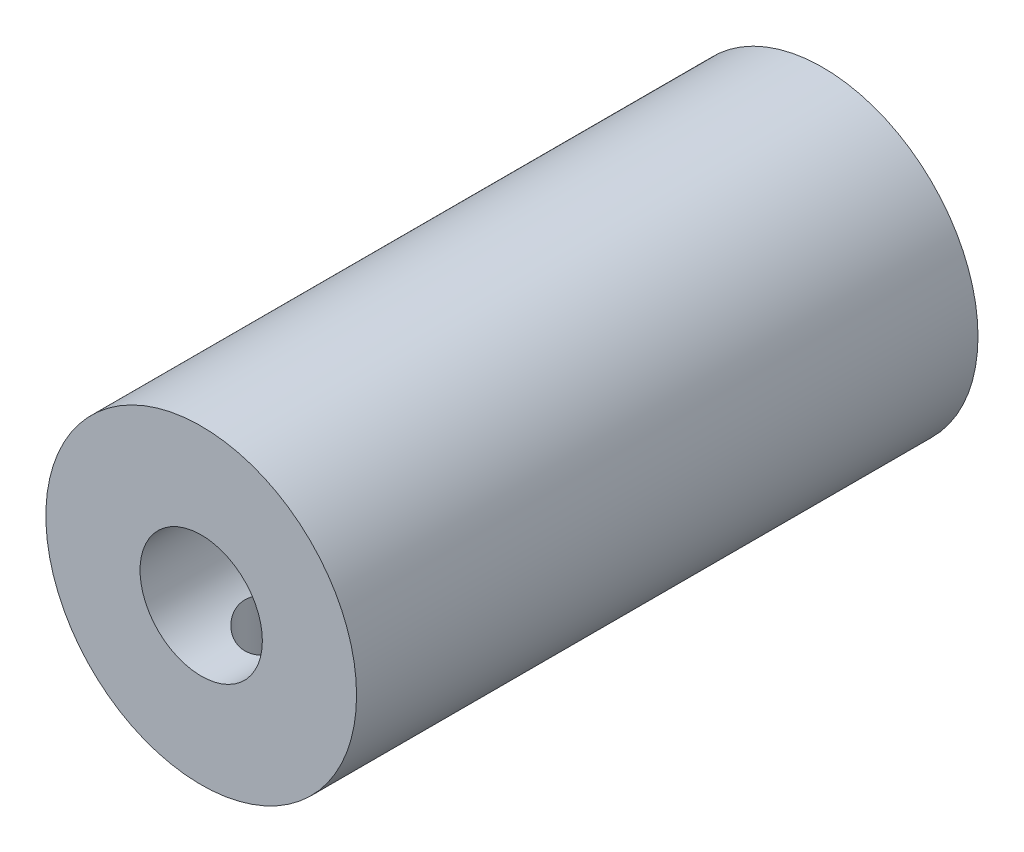
SolidWorks part; units mm, degrees
ref_plane "Front Plane" through (0, 0, 0) normal (0, 0, 1) x (1, 0, 0)
ref_plane "Top Plane" through (0, 0, 0) normal (0, 1, 0) x (1, 0, 0)
ref_plane "Right Plane" through (0, 0, 0) normal (1, 0, 0) x (0, 0, -1)
sketch "Sketch1" plane through (0, 0, 0) normal (0, 0, 1) x (1, 0, 0)
  circle A0 centre (0, 0) radius 6.35
  dimension "D1" = 12.7
extrude "Boss-Extrude1" add sketch "Sketch1" along normal blind 25.4
sketch "Sketch2" plane through (0, 0, 25.4) normal (0, 0, 1) x (1, 0, 0)
  circle A0 centre (0, 0) radius 2.5
  dimension "D1" = 5
extrude "Cut-Extrude1" cut sketch "Sketch2" against normal blind 12.7
sketch "Sketch3" plane through (0, 0, 0) normal (0, 0, -1) x (-1, 0, 0)
  circle A0 centre (0, 0) radius 3.175
  dimension "D1" = 6.35
extrude "Cut-Extrude2" cut sketch "Sketch3" against normal blind 12.7
sketch "Sketch4" plane through (0, 0, 0) normal (0, 1, 0) x (1, 0, 0)
  line L0 (-6.35, -25.4) -> (6.35, -25.4) construction
  line L1 (6.35, 0) -> (-6.35, 0) construction
  line L2 (0, -3.175) -> (0, 0) construction
  line L3 (0, 0) -> (0, -22.225) construction
  circle A0 centre (0, -22.225) radius 1.3891
  circle A1 centre (0, -3.175) radius 1.3891
  dimension "D1" = 2.7781
  dimension "D2" = 2.7781
  dimension "D3" = 3.175
  dimension "D4" = 3.175
extrude "Cut-Extrude4" cut sketch "Sketch4" against normal up to surface (6.35 mm away)
